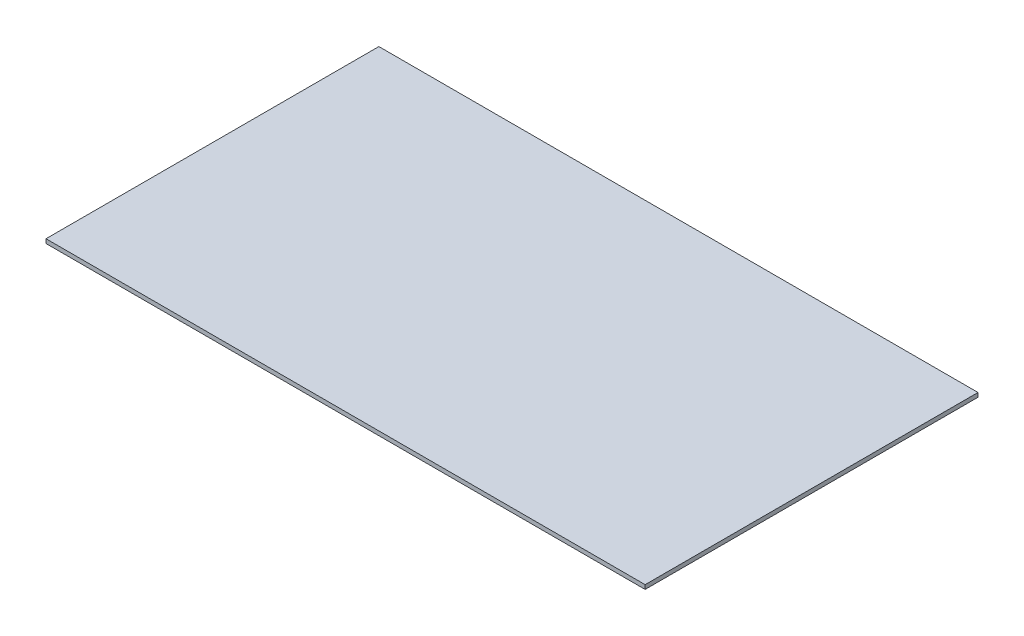
SolidWorks part; units mm, degrees
material "Balsa"
ref_plane "Front Plane" through (0, 0, 0) normal (0, 0, 1) x (1, 0, 0)
ref_plane "Top Plane" through (0, 0, 0) normal (0, 1, 0) x (1, 0, 0)
ref_plane "Right Plane" through (0, 0, 0) normal (1, 0, 0) x (0, 0, -1)
sketch "Sketch1" plane through (0, 0, 0) normal (0, 1, 0) x (1, 0, 0)
  line L1 (-457.2, 254) -> (457.2, 254)
  line L2 (-457.2, 254) -> (-457.2, -254)
  line L3 (-457.2, -254) -> (457.2, -254)
  line L4 (457.2, 254) -> (457.2, -254)
  line L5 (-457.2, 254) -> (457.2, -254) construction
  line L6 (-457.2, -254) -> (457.2, 254) construction
  point P0 (0, 0)
  dimension "D1" = 914.4
  dimension "D2" = 508
extrude "Boss-Extrude1" add sketch "Sketch1" along normal blind 6.35
sketch "Sketch2" plane through (0, 6.35, 0) normal (0, 1, 0) x (1, 0, 0)
  line L0 (-457.2, -254) -> (457.2, -254)
  line L1 (-457.2, -254) -> (-457.2, 254)
  line L2 (-431.8, -254) -> (-431.8, 254)
  line L3 (-406.4, -254) -> (-406.4, 254)
  line L4 (-381, -254) -> (-381, 254)
  line L5 (-355.6, -254) -> (-355.6, 254)
  line L6 (-330.2, -254) -> (-330.2, 254)
  line L7 (-304.8, -254) -> (-304.8, 254)
  line L8 (-279.4, -254) -> (-279.4, 254)
  line L9 (-254, -254) -> (-254, 254)
  line L10 (-228.6, -254) -> (-228.6, 254)
  line L11 (-203.2, -254) -> (-203.2, 254)
  line L12 (-177.8, -254) -> (-177.8, 254)
  line L13 (-152.4, -254) -> (-152.4, 254)
  line L14 (-127, -254) -> (-127, 254)
  line L15 (-101.6, -254) -> (-101.6, 254)
  line L16 (-76.2, -254) -> (-76.2, 254)
  line L17 (-50.8, -254) -> (-50.8, 254)
  line L18 (-25.4, -254) -> (-25.4, 254)
  line L19 (0, -254) -> (0, 254)
  line L20 (25.4, -254) -> (25.4, 254)
  line L21 (50.8, -254) -> (50.8, 254)
  line L22 (76.2, -254) -> (76.2, 254)
  line L23 (101.6, -254) -> (101.6, 254)
  line L24 (127, -254) -> (127, 254)
  line L25 (152.4, -254) -> (152.4, 254)
  line L26 (177.8, -254) -> (177.8, 254)
  line L27 (203.2, -254) -> (203.2, 254)
  line L28 (228.6, -254) -> (228.6, 254)
  line L29 (254, -254) -> (254, 254)
  line L30 (279.4, -254) -> (279.4, 254)
  line L31 (304.8, -254) -> (304.8, 254)
  line L32 (330.2, -254) -> (330.2, 254)
  line L33 (355.6, -254) -> (355.6, 254)
  line L34 (381, -254) -> (381, 254)
  line L35 (406.4, -228.6) -> (406.4, 241.3)
  line L36 (431.8, -228.6) -> (431.8, 241.3)
  line L37 (457.2, -254) -> (457.2, 254)
  line L38 (-457.2, -228.6) -> (457.2, -228.6)
  line L39 (-457.2, -203.2) -> (457.2, -203.2)
  line L40 (-457.2, -177.8) -> (457.2, -177.8)
  line L41 (-457.2, -152.4) -> (457.2, -152.4)
  line L42 (-457.2, -127) -> (457.2, -127)
  line L43 (-457.2, -101.6) -> (457.2, -101.6)
  line L44 (-457.2, -76.2) -> (457.2, -76.2)
  line L45 (-457.2, -50.8) -> (457.2, -50.8)
  line L46 (-457.2, -25.4) -> (457.2, -25.4)
  line L47 (-457.2, 0) -> (457.2, 0)
  line L48 (-457.2, 25.4) -> (457.2, 25.4)
  line L49 (-457.2, 50.8) -> (457.2, 50.8)
  line L50 (-457.2, 76.2) -> (457.2, 76.2)
  line L51 (-457.2, 101.6) -> (457.2, 101.6)
  line L52 (-457.2, 127) -> (457.2, 127)
  line L53 (-457.2, 152.4) -> (457.2, 152.4)
  line L54 (-457.2, 177.8) -> (457.2, 177.8)
  line L55 (-457.2, 203.2) -> (457.2, 203.2)
  line L56 (-457.2, 228.6) -> (457.2, 228.6)
  dimension "D1" = 37
  dimension "D3" = 25.4
  dimension "D2" = 20
sketch "Sketch3" plane through (0, 6.35, 0) normal (0, 1, 0) x (1, 0, 0)
  line L0 (457.2, -239) -> (381, -239) construction
  line L1 (457.2, -254) -> (457.2, 254) construction
  line L2 (381, -254) -> (381, 254) construction
  line L3 (-457.2, -254) -> (457.2, -254) construction
  text T0 "PRATIK PALWAI \r\nUCI MECH ENG '28 " font "Consolas" height 5
  dimension "D1" = 15
hole_wizard "CSK for M3 Flat Head Machine Screw"
sketch "Sketch4" [suppressed] plane through (0, 6.35, 0) normal (0, 1, 0) x (1, 0, 0)
  point P7 (-452.2, 215)
  point P9 (-452.2, 205)
  point P11 (-428.6, 215)
  point P13 (-428.6, 205)
  point P15 (-452.2, 5)
  point P17 (-428.6, 5)
  point P19 (-428.6, -5)
  point P21 (-452.2, -5)
  point P23 (-452.2, -205)
  point P25 (-452.2, -215)
  point P27 (-428.6, -205)
  point P29 (-428.6, -215)
  point P55 (-405, -225.4)
  point P57 (-395, -225.4)
  point P59 (-395, -249)
  point P61 (-405, -249)
  point P63 (-205, -225.4)
  point P65 (-195, -225.4)
  point P67 (-195, -249)
  point P69 (-205, -249)
  point P71 (-5, -225.4)
  point P73 (5, -225.4)
  point P75 (5, -249)
  point P77 (-5, -249)
  point P79 (195, -225.4)
  point P81 (195, -249)
  point P83 (205, -249)
  point P85 (205, -225.4)
  point P87 (395, -225.4)
  point P89 (405, -225.4)
  point P91 (405, -249)
  point P93 (395, -249)
  point P97 (395, -212.7)
  point P99 (395, -236.3)
  point P119 (428.6, -205)
  point P121 (428.6, -215)
  point P123 (452.2, -205)
  point P125 (452.2, -215)
  point P127 (428.6, 5)
  point P129 (428.6, -5)
  point P131 (452.2, 5)
  point P133 (452.2, -5)
  point P135 (428.6, 215)
  point P137 (428.6, 205)
  point P139 (452.2, 215)
  point P141 (452.2, 205)
  point P161 (395, 236.3)
  point P163 (395, 212.7)
  point P167 (395, 249)
  point P169 (405, 249)
  point P171 (405, 225.4)
  point P173 (395, 225.4)
  point P175 (195, 249)
  point P177 (205, 249)
  point P179 (205, 225.4)
  point P181 (195, 225.4)
  point P183 (-5, 249)
  point P185 (5, 249)
  point P187 (5, 225.4)
  point P189 (-5, 225.4)
  point P191 (-205, 249)
  point P193 (-195, 249)
  point P195 (-195, 225.4)
  point P197 (-205, 225.4)
  point P199 (-395, 225.4)
  point P201 (-405, 225.4)
  point P203 (-405, 249)
  point P205 (-395, 249)
  point P207 (-395, 249)
  point P213 (-395, 212.7)
sketch "Sketch5" [suppressed] plane through (-452.2, 6.35, -215) normal (1, 0, 0) x (0, 0, 1)
  line L0 (0, 0) -> (0, 6.35)
  line L1 (0, 6.35) -> (1.7, 6.35)
  line L2 (1.7, 6.35) -> (1.7, 1.45)
  line L3 (1.7, 1.45) -> (3.15, 0)
  line L4 (3.15, 0) -> (0, 0)
  line L5 (-1.7, 1.45) -> (-3.15, 0) construction
  line L6 (0, -6.35) -> (0, 107.95) construction
  dimension "Thru Hole Dia." = 3.4
  dimension "Thru Hole Depth" = 6.35
  dimension "Near C'Sink Dia." = 6.3
  dimension "Near C'Sink Angle" = 90
